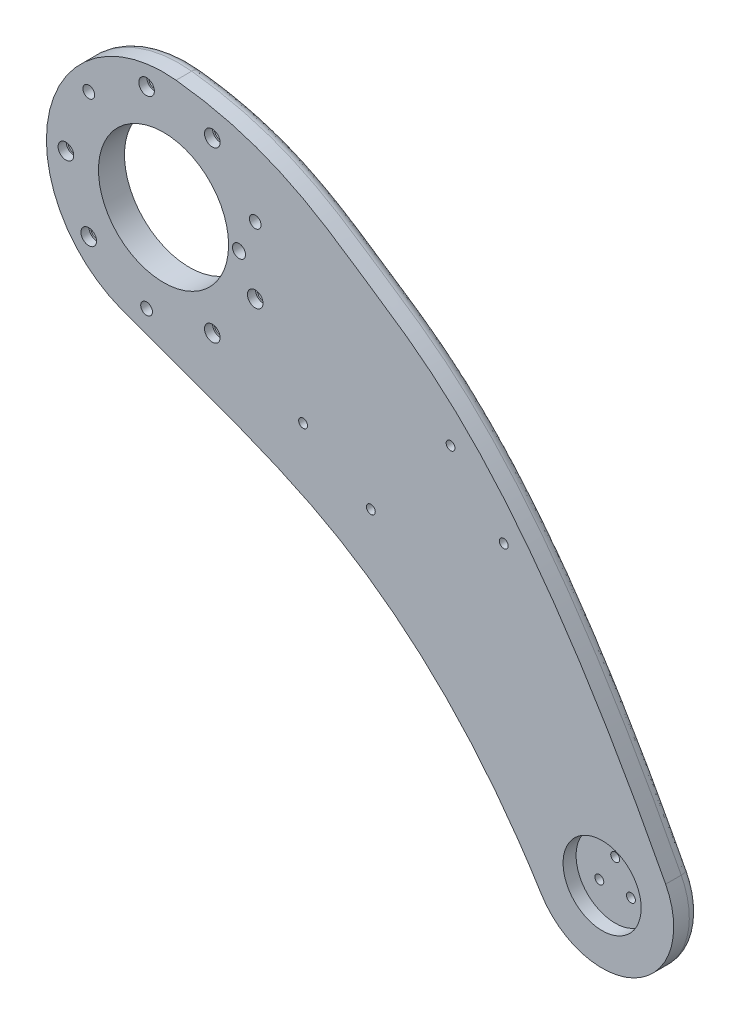
SolidWorks part; units mm, degrees
ref_plane "Front Plane" through (0, 0, 0) normal (0, 0, 1) x (1, 0, 0)
ref_plane "Top Plane" through (0, 0, 0) normal (0, 1, 0) x (1, 0, 0)
ref_plane "Right Plane" through (0, 0, 0) normal (1, 0, 0) x (0, 0, -1)
sketch "Sketch5" plane through (0, 0, 0) normal (0, 0, 1) x (1, 0, 0)
  line L0 (0, 0) -> (261.9378, 0) construction
  line L1 (0, 0) -> (168.5298, -141.4133) construction
  line L2 (35.2385, -340.5991) -> (84.4116, -340.5991)
  line L3 (168.5298, -141.4133) -> (168.5298, -111.4133) construction
  line L4 (168.5298, -141.4133) -> (-104.0059, -141.4133) construction
  line L5 (168.5298, -141.4133) -> (53.5298, -340.5991) construction
  line L6 (0, 0) -> (0, 30) construction
  line L7 (176.6521, -105.5799) -> (190.8662, -125.3716) construction
  line L8 (160.4074, -105.5799) -> (146.1934, -125.3716) construction
  circle A0 centre (0, 0) radius 37.5 construction
  circle A1 centre (0, 0) radius 45
  circle A2 centre (0, 0) radius 25
  circle A3 centre (29, 0) radius 2.5
  circle A5 centre (-37.5, 0) radius 2.25
  circle A6 centre (-28.7267, 24.1045) radius 2.25
  circle A7 centre (-6.5118, 36.9303) radius 2.25
  circle A8 centre (18.75, 32.476) radius 2.25
  circle A9 centre (35.2385, 12.8258) radius 2.25
  circle A10 centre (35.2385, -12.8258) radius 2.25
  circle A11 centre (18.75, -32.476) radius 2.25
  circle A12 centre (-6.5118, -36.9303) radius 2.25
  circle A13 centre (-28.7267, -24.1045) radius 2.25
  circle A14 centre (168.5298, -141.4133) radius 27.5
  circle A15 centre (168.5298, -141.4133) radius 18.5625
  circle A16 centre (168.5298, -141.4133) radius 16.9375
  circle A17 centre (168.5298, -111.4133) radius 10 construction
  circle A18 centre (0, 30) radius 10 construction
  spline S0 degree 3 poles (141.3314, -145.475) (148.882, -231.4219) (65.2218, -271.0706) (35.2385, -340.5991) knots 0 0 0 0 1 1 1 1
  spline S1 degree 3 poles (193.5611, -152.8011) (170.0243, -223.2307) (106.798, -269.8913) (84.4116, -340.5991) knots 0 0 0 0 1 1 1 1
  spline S2 degree 3 poles (4.8232, 44.7408) (39.4666, 41.0061) (63.7182, 23.7064) (102.0622, -1.507) (143.1831, -32.9689) (192.9333, -128.7358) knots 0 0 0 0 0.393439 0.493439 1 1 1 1
  spline S3 degree 3 poles (-16.0508, -42.0401) (9.9702, -51.9748) (77.4499, -71.8001) (124.3669, -122.0972) (145.1049, -155.8189) knots 0 0 0 0 0.431451 1 1 1 1
  point P29 (0, 0)
extrude "Boss-Extrude1" add sketch "Sketch5" along normal blind 10 contours A1 S3 S0 A14 S2 | A1 A13 A12 A11 A10 A9 A8 A7 A6 A5 A3 A2 | S0 S3 A14 | A14 A15
sketch "Sketch6" plane through (0, 0, 10) normal (0, 0, 1) x (1, 0, 0)
  circle A0 centre (168.5298, -141.4133) radius 15
  dimension "D1" = 30
extrude "Cut-Extrude1" cut sketch "Sketch6" against normal blind 5
fillet "Fillet1" radius 4 4 edges at (-43.7521, 10.524, 0) (182.0802, -165.3431, 0)
sketch "Sketch7" plane through (0, 0, 10) normal (0, 0, 1) x (1, 0, 0)
  line L0 (0, 0) -> (168.5298, -141.4133) construction
  line L1 (79.6603, -60.6369) -> (110.2978, -24.1246) construction
  line L2 (53.6231, -44.9951) -> (86.7625, -5.5012) construction
  line L3 (103.7465, -78.6039) -> (130.7244, -46.4529) construction
  circle A0 centre (86.7625, -5.5012) radius 3.5 construction
  circle A1 centre (110.2978, -24.1246) radius 3.5 construction
  circle A2 centre (130.7244, -46.4529) radius 3.5 construction
  circle A3 centre (86.7625, -5.5012) radius 1.7 construction
  circle A4 centre (110.2978, -24.1246) radius 1.7
  circle A5 centre (130.7244, -46.4529) radius 1.7
  circle A6 centre (53.6231, -44.9951) radius 1.7
  circle A7 centre (79.6603, -60.6369) radius 1.7
  circle A8 centre (103.7465, -78.6039) radius 1.7 construction
  dimension "D5" = 7
  dimension "D6" = 7
  dimension "D7" = 7
  dimension "D8" = 3.4
  dimension "D9" = 3.4
  dimension "D10" = 3.4
  dimension "D11" = 3.4
  dimension "D12" = 3.4
  dimension "D13" = 3.4
  dimension "D1" = 30
  dimension "D2" = 30
  dimension "D4" = 70
extrude "Cut-Extrude2" cut sketch "Sketch7" against normal through all
sketch "Sketch8" plane through (0, 0, 10) normal (0, 0, 1) x (1, 0, 0)
  circle A1 centre (-37.5, 0) radius 3
  circle A2 centre (18.7497, -32.4765) radius 3
  circle A3 centre (18.75, 32.476) radius 3
  circle A4 centre (-28.7269, -24.1046) radius 3
  circle A5 centre (35.2383, -12.8265) radius 3
  circle A6 centre (-6.5114, 36.93) radius 3
  dimension "D1" = 6
  dimension "D2" = 6
  dimension "D3" = 6
  dimension "D4" = 6
  dimension "D5" = 6
  dimension "D6" = 6
extrude "Cut-Extrude3" cut sketch "Sketch8" against normal blind 3.1
sketch "Sketch9" plane through (0, 0, 0) normal (0, 0, -1) x (-1, 0, 0)
  circle A0 centre (28.7264, 24.1044) radius 3
  circle A1 centre (6.5118, -36.9303) radius 3
  circle A2 centre (-35.2385, 12.8258) radius 3
  dimension "D1" = 6
  dimension "D2" = 6
  dimension "D3" = 6
extrude "Cut-Extrude4" cut sketch "Sketch9" against normal blind 3.1
sketch "Sketch10" plane through (0, 0, 0) normal (0, 0, -1) x (-1, 0, 0)
  line L0 (-168.5298, -141.4133) -> (-168.5298, -134.4089) construction
  circle A0 centre (-168.5298, -141.4133) radius 14.94 construction
  circle A1 centre (-168.5298, -134.4089) radius 1.7
  circle A2 centre (-162.4638, -144.9155) radius 1.7
  circle A3 centre (-174.5958, -144.9155) radius 1.7
  point P12 (-168.5298, -141.4133)
  dimension "D1" = 29.88
  dimension "D3" = 3.4
  dimension "D2" = 7.0044
  dimension "D4" = 3
extrude "Cut-Extrude5" cut sketch "Sketch10" against normal blind 40
sketch "Sketch11" plane through (0, 0, 0) normal (0, 0, -1) x (-1, 0, 0)
  circle A0 centre (-168.5298, -134.4089) radius 3
  circle A1 centre (-162.4638, -144.9155) radius 3
  circle A2 centre (-174.5958, -144.9155) radius 3
  dimension "D1" = 6
  dimension "D2" = 6
  dimension "D3" = 6
extrude "Cut-Extrude6" [suppressed] cut sketch "Sketch11" against normal blind 3
